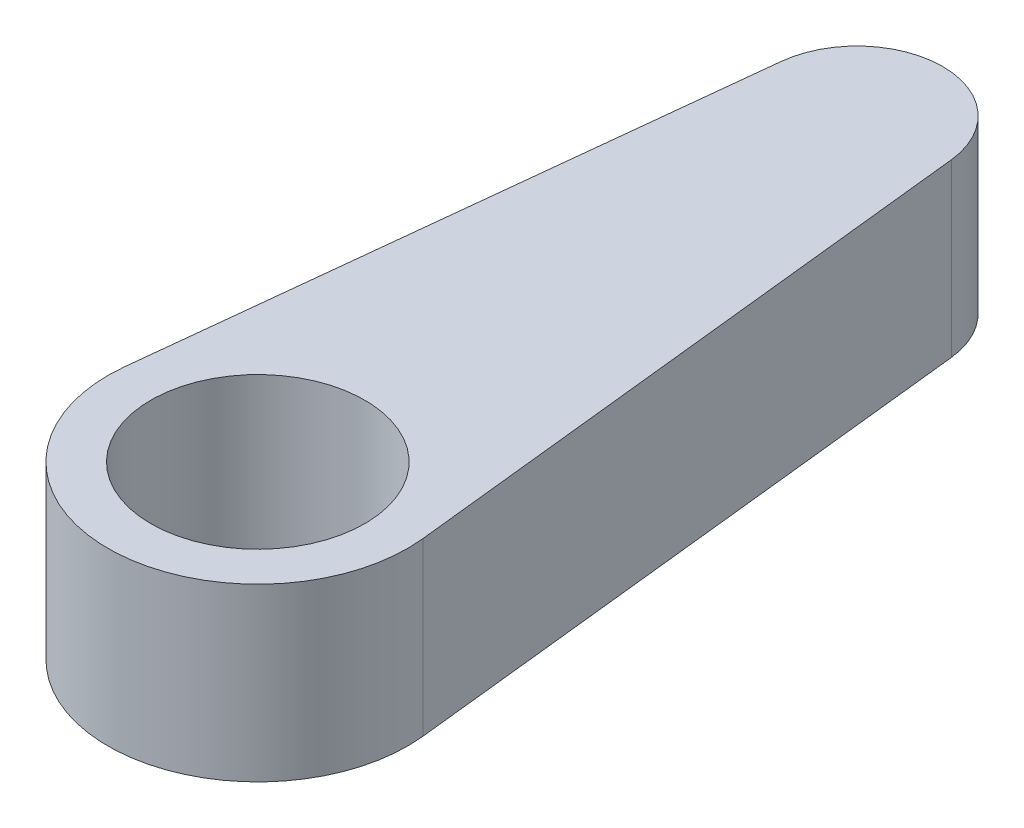
SolidWorks part; units mm, degrees
ref_plane "前视基准面" through (0, 0, 0) normal (0, 0, 1) x (1, 0, 0)
ref_plane "上视基准面" through (0, 0, 0) normal (0, 1, 0) x (1, 0, 0)
ref_plane "右视基准面" through (0, 0, 0) normal (1, 0, 0) x (0, 0, -1)
other "Configuration Table"
sketch "草图1" plane through (0, 0, 0) normal (0, 1, 0) x (1, 0, 0)
  line L0 (0, 0) -> (0, 14)
  line L1 (-1.9885, 14.2143) -> (-3.4799, 0.375)
  line L2 (1.9885, 14.2143) -> (3.4799, 0.375)
  circle A0 centre (0, 0) radius 3.5
  circle A1 centre (0, 14) radius 2
  dimension "D1" = 7
  dimension "D3" = 4
  dimension "D2" = 14
extrude "凸台-拉伸1" add sketch "草图1" along normal blind 4
sketch "草图2" plane through (0, 4, 0) normal (0, 1, 0) x (1, 0, 0)
  line L2 (-1.9885, 14.2143) -> (-3.4799, 0.375)
  line L3 (3.4799, 0.375) -> (1.9885, 14.2143)
  line L4 (-1.9885, 14.2143) -> (-3.4799, 0.375)
  line L5 (3.4799, 0.375) -> (1.9885, 14.2143)
  circle A0 centre (0, 0) radius 2.5
  arc A2 (-3.4799, 0.375) -> (3.4799, 0.375) centre (0, 0) ccw
  arc A3 (1.9885, 14.2143) -> (-1.9885, 14.2143) centre (0, 14) ccw
  arc A4 (-3.4799, 0.375) -> (3.4799, 0.375) centre (0, 0) ccw
  arc A5 (1.9885, 14.2143) -> (-1.9885, 14.2143) centre (0, 14) ccw
  dimension "D1" = 0
extrude "切除-拉伸1" cut sketch "草图2" against normal up to next contours A0
